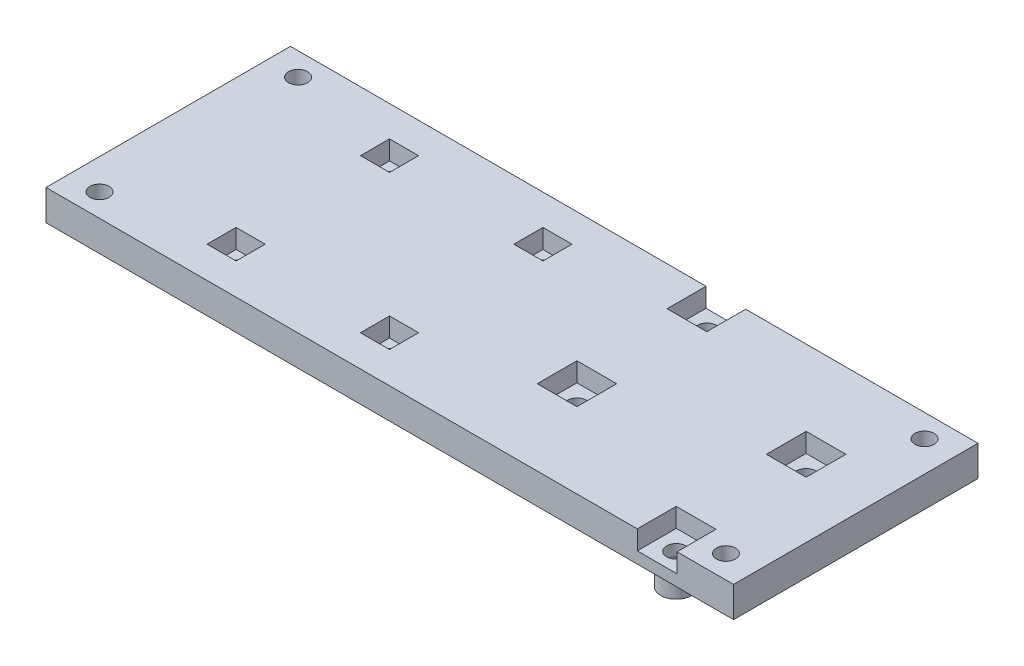
SolidWorks part; units mm, degrees
ref_plane "Front Plane" through (0, 0, 0) normal (0, 0, 1) x (1, 0, 0)
ref_plane "Top Plane" through (0, 0, 0) normal (0, 1, 0) x (1, 0, 0)
ref_plane "Right Plane" through (0, 0, 0) normal (1, 0, 0) x (0, 0, -1)
sketch "Sketch1" plane through (0, 0, 0) normal (0, 1, 0) x (1, 0, 0)
  line L1 (-37.7046, -6.5531) -> (76.5954, -6.5531)
  line L2 (-37.7046, -6.5531) -> (-37.7046, 34.0869)
  line L3 (-37.7046, 34.0869) -> (76.5954, 34.0869)
  line L4 (76.5954, -6.5531) -> (76.5954, 34.0869)
  dimension "D1" = 40.64
  dimension "D2" = 114.3
extrude "Boss-Extrude1" add sketch "Sketch1" along normal blind 5.08
sketch "Sketch2" plane through (0, 5.08, 0) normal (0, 1, 0) x (1, 0, 0)
  line L0 (76.5954, 34.0869) -> (-37.7046, 34.0869) construction
  line L1 (-37.7046, -6.5531) -> (76.5954, -6.5531) construction
  line L2 (76.5954, -6.5531) -> (76.5954, 34.0869) construction
  line L3 (-37.7046, 34.0869) -> (-37.7046, -6.5531) construction
  circle A0 centre (-32.6246, 30.2769) radius 1.5875
  circle A1 centre (71.5154, 30.2769) radius 1.5875
  circle A2 centre (71.5154, -2.7431) radius 1.5875
  circle A3 centre (-32.6246, -2.7431) radius 1.5875
  point P10 (0, 0)
  dimension "D1" = 3.175
  dimension "D2" = 3.81
  dimension "D3" = 3.81
  dimension "D4" = 3.81
  dimension "D5" = 3.81
  dimension "D6" = 5.08
  dimension "D7" = 5.08
  dimension "D8" = 5.08
  dimension "D9" = 5.08
extrude "Cut-Extrude1" cut sketch "Sketch2" against normal through all
sketch "Sketch5" plane through (0, 0, 0) normal (0, -1, 0) x (1, 0, 0)
  line L2 (-37.7046, 6.5531) -> (76.5954, 6.5531) construction
  line L3 (76.5954, -34.0869) -> (-37.7046, -34.0869) construction
  line L4 (76.5954, 6.5531) -> (76.5954, -34.0869) construction
  circle A0 centre (63.8954, 3.3781) radius 1.5875
  circle A1 centre (34.6854, -9.3219) radius 1.5875
  circle A2 centre (63.8954, -18.2119) radius 1.5875
  circle A3 centre (34.6854, -30.9119) radius 1.5875
  point P8 (60.8005, 3.4344)
  point P9 (36.55, -7.9176)
  point P10 (22.5132, 4.2335)
  point P11 (17.325, 2.9512)
  point P12 (0, -8.4665)
  point P13 (65.76, -19.4152)
  point P14 (65.76, 3.5897)
  dimension "D1" = 3.175
  dimension "D2" = 29.21
  dimension "D3" = 29.21
  dimension "D4" = 12.7
  dimension "D5" = 12.7
  dimension "D6" = 3.175
  dimension "D7" = 3.175
  dimension "D8" = 12.7
  dimension "D9" = 12.7
extrude "Cut-Extrude2" cut sketch "Sketch5" against normal through all
sketch "Sketch6" plane through (0, 0, 0) normal (0, -1, 0) x (1, 0, 0)
  circle A0 centre (63.8954, 3.3781) radius 2.5753
  circle A1 centre (63.8954, -18.2119) radius 2.4673
  circle A2 centre (34.6854, -9.3219) radius 2.5293
  circle A3 centre (34.6854, -30.9119) radius 2.4916
  circle A4 centre (63.8954, 3.3781) radius 1.7557
  circle A5 centre (63.8954, -18.2119) radius 1.5875
  circle A6 centre (34.6854, -9.3219) radius 1.5875
  circle A7 centre (34.6854, -30.9119) radius 1.5875
extrude "Boss-Extrude2" add sketch "Sketch6" along normal blind 3.175
sketch "Sketch7" plane through (0, 0, 0) normal (0, -1, 0) x (1, 0, 0)
  line L0 (76.5954, -13.8065) -> (-37.7046, -13.7669) construction
  line L1 (-37.7046, -34.0869) -> (-37.7046, 6.5531) construction
  circle A0 centre (11.7643, -1.084) radius 1.27
  circle A1 centre (11.7717, -26.584) radius 1.27
  circle A2 centre (-13.7357, -1.084) radius 1.27
  circle A3 centre (-13.7283, -26.584) radius 1.27
  dimension "D1" = 2.54
  dimension "D2" = 25.5
  dimension "D3" = 25.5
  dimension "D4" = 25.5
  dimension "D5" = 25.5
  dimension "D6" = 0
  dimension "D7" = 12.7
extrude "Cut-Extrude3" cut sketch "Sketch7" against normal through all
sketch "Sketch8" plane through (0, 0, 0) normal (0, -1, 0) x (1, 0, 0)
  circle A0 centre (11.7643, -1.084) radius 1.27
  circle A1 centre (11.7717, -26.584) radius 1.27
  circle A2 centre (-13.7283, -26.584) radius 1.27
  circle A3 centre (-13.7357, -1.084) radius 1.27
  circle A4 centre (-13.7357, -1.084) radius 2.0374
  circle A5 centre (11.7643, -1.084) radius 2.0989
  circle A6 centre (11.7717, -26.584) radius 1.9571
  circle A7 centre (-13.7283, -26.584) radius 2.0852
extrude "Boss-Extrude3" add sketch "Sketch8" along normal blind 3.175
sketch "Sketch9" plane through (0, 5.08, 0) normal (0, 1, 0) x (1, 0, 0)
  line L1 (60.5934, 14.9099) -> (67.1974, 14.9099)
  line L2 (60.5934, 14.9099) -> (60.5934, 21.5139)
  line L3 (60.5934, 21.5139) -> (67.1974, 21.5139)
  line L4 (67.1974, 14.9099) -> (67.1974, 21.5139)
  line L5 (60.5934, 14.9099) -> (67.1974, 21.5139) construction
  line L6 (60.5934, 21.5139) -> (67.1974, 14.9099) construction
  line L7 (60.5934, -6.6801) -> (67.1974, -6.6801)
  line L8 (60.5934, -6.6801) -> (60.5934, -0.0761)
  line L9 (60.5934, -0.0761) -> (67.1974, -0.0761)
  line L10 (67.1974, -6.6801) -> (67.1974, -0.0761)
  line L11 (60.5934, -6.6801) -> (67.1974, -0.0761) construction
  line L12 (60.5934, -0.0761) -> (67.1974, -6.6801) construction
  line L13 (31.3834, 6.0199) -> (37.9874, 6.0199)
  line L14 (31.3834, 6.0199) -> (31.3834, 12.6239)
  line L15 (31.3834, 12.6239) -> (37.9874, 12.6239)
  line L16 (37.9874, 6.0199) -> (37.9874, 12.6239)
  line L17 (31.3834, 6.0199) -> (37.9874, 12.6239) construction
  line L18 (31.3834, 12.6239) -> (37.9874, 6.0199) construction
  line L19 (31.3834, 27.6099) -> (37.9874, 27.6099)
  line L20 (31.3834, 27.6099) -> (31.3834, 34.2139)
  line L21 (31.3834, 34.2139) -> (37.9874, 34.2139)
  line L22 (37.9874, 27.6099) -> (37.9874, 34.2139)
  line L23 (31.3834, 27.6099) -> (37.9874, 34.2139) construction
  line L24 (31.3834, 34.2139) -> (37.9874, 27.6099) construction
  line L25 (-11.3153, 28.997) -> (-16.1413, 28.997)
  line L26 (-11.3153, 28.997) -> (-11.3153, 24.171)
  line L27 (-11.3153, 24.171) -> (-16.1413, 24.171)
  line L28 (-16.1413, 28.997) -> (-16.1413, 24.171)
  line L29 (-11.3153, 28.997) -> (-16.1413, 24.171) construction
  line L30 (-11.3153, 24.171) -> (-16.1413, 28.997) construction
  line L31 (14.1847, 28.997) -> (9.3587, 28.997)
  line L32 (14.1847, 28.997) -> (14.1847, 24.171)
  line L33 (14.1847, 24.171) -> (9.3587, 24.171)
  line L34 (9.3587, 28.997) -> (9.3587, 24.171)
  line L35 (14.1847, 28.997) -> (9.3587, 24.171) construction
  line L36 (14.1847, 24.171) -> (9.3587, 28.997) construction
  line L37 (-16.1487, 3.497) -> (-11.3227, 3.497)
  line L38 (-16.1487, 3.497) -> (-16.1487, -1.329)
  line L39 (-16.1487, -1.329) -> (-11.3227, -1.329)
  line L40 (-11.3227, 3.497) -> (-11.3227, -1.329)
  line L41 (-16.1487, 3.497) -> (-11.3227, -1.329) construction
  line L42 (-16.1487, -1.329) -> (-11.3227, 3.497) construction
  line L43 (14.1773, 3.497) -> (9.3513, 3.497)
  line L44 (14.1773, 3.497) -> (14.1773, -1.329)
  line L45 (14.1773, -1.329) -> (9.3513, -1.329)
  line L46 (9.3513, 3.497) -> (9.3513, -1.329)
  line L47 (14.1773, 3.497) -> (9.3513, -1.329) construction
  line L48 (14.1773, -1.329) -> (9.3513, 3.497) construction
  point P0 (63.8954, 18.2119)
  point P6 (63.8954, -3.3781)
  point P12 (34.6854, 9.3219)
  point P18 (34.6854, 30.9119)
  point P24 (-13.7283, 26.584)
  point P30 (11.7717, 26.584)
  point P36 (-13.7357, 1.084)
  point P42 (11.7643, 1.084)
  point P48 (-11.3227, 1.084)
  dimension "D1" = 6.604
  dimension "D2" = 6.604
  dimension "D3" = 4.826
  dimension "D4" = 4.826
  dimension "D5" = 4.826
  dimension "D6" = 4.826
extrude "Cut-Extrude4" cut sketch "Sketch9" against normal blind 3.175
